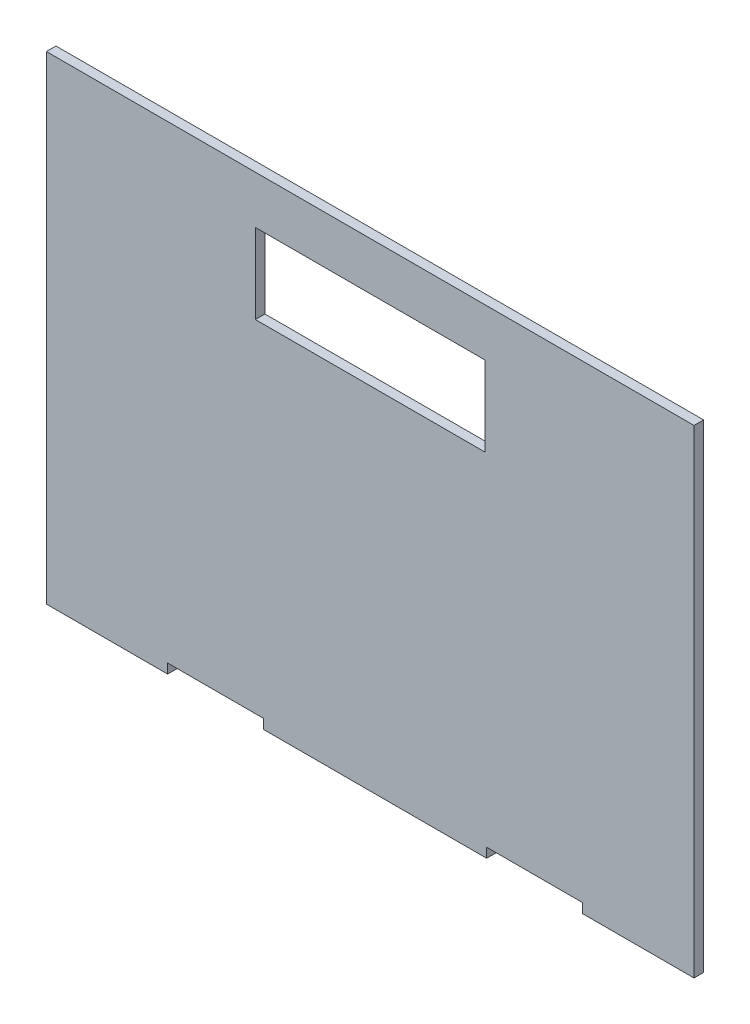
SolidWorks part; units mm, degrees
ref_plane "Front Plane" through (0, 0, 0) normal (0, 0, 1) x (1, 0, 0)
ref_plane "Top Plane" through (0, 0, 0) normal (0, 1, 0) x (1, 0, 0)
ref_plane "Right Plane" through (0, 0, 0) normal (1, 0, 0) x (0, 0, -1)
sketch "Sketch1" plane through (0, 0, 0) normal (0, 0, 1) x (1, 0, 0)
  line L1 (-101.5, 75) -> (101.5, 75)
  line L2 (-101.5, 75) -> (-101.5, -75)
  line L3 (-101.5, -75) -> (101.5, -75)
  line L4 (101.5, 75) -> (101.5, -75)
  line L5 (-101.5, 75) -> (101.5, -75) construction
  line L6 (-101.5, -75) -> (101.5, 75) construction
  point P0 (0, 0)
  dimension "D1" = 150
  dimension "D2" = 203
extrude "Boss-Extrude1" add sketch "Sketch1" along normal blind 3
sketch "Sketch2" plane through (0, 0, 3) normal (0, 0, 1) x (1, 0, 0)
  line L0 (0, 75) -> (0, -75) construction
  line L1 (101.5, 75) -> (-101.5, 75) construction
  line L2 (-101.5, -75) -> (101.5, -75) construction
  line L4 (-36, 60) -> (36, 60)
  line L5 (-36, 60) -> (-36, 35)
  line L6 (-36, 35) -> (36, 35)
  line L7 (36, 60) -> (36, 35)
  line L8 (-36, 60) -> (36, 35) construction
  line L9 (-36, 35) -> (36, 60) construction
  point P6 (0, 47.5)
  dimension "D1" = 25
  dimension "D2" = 72
  dimension "D3" = 15
extrude "Cut-Extrude1" cut sketch "Sketch2" against normal blind 10
sketch "Sketch3" plane through (0, 0, 3) normal (0, 0, 1) x (1, 0, 0)
  line L0 (0, 0) -> (0, -75) construction
  line L1 (-101.5, -75) -> (101.5, -75) construction
  line L2 (-48.5, -75) -> (-48.5, -72) construction
  line L3 (-63.5, -75) -> (-33.5, -75)
  line L4 (-63.5, -75) -> (-63.5, -72)
  line L5 (-63.5, -72) -> (-33.5, -72)
  line L6 (-33.5, -75) -> (-33.5, -72)
  line L7 (-101.5, 75) -> (-101.5, -75) construction
  line L8 (36.5, -75) -> (36.5, -72)
  line L9 (36.5, -75) -> (66.5, -75)
  line L10 (66.5, -75) -> (66.5, -72)
  line L11 (36.5, -72) -> (66.5, -72)
  dimension "D1" = 30
  dimension "D2" = 3
  dimension "D3" = 53
  dimension "D4" = 2
extrude "Cut-Extrude2" cut sketch "Sketch3" against normal blind 10
